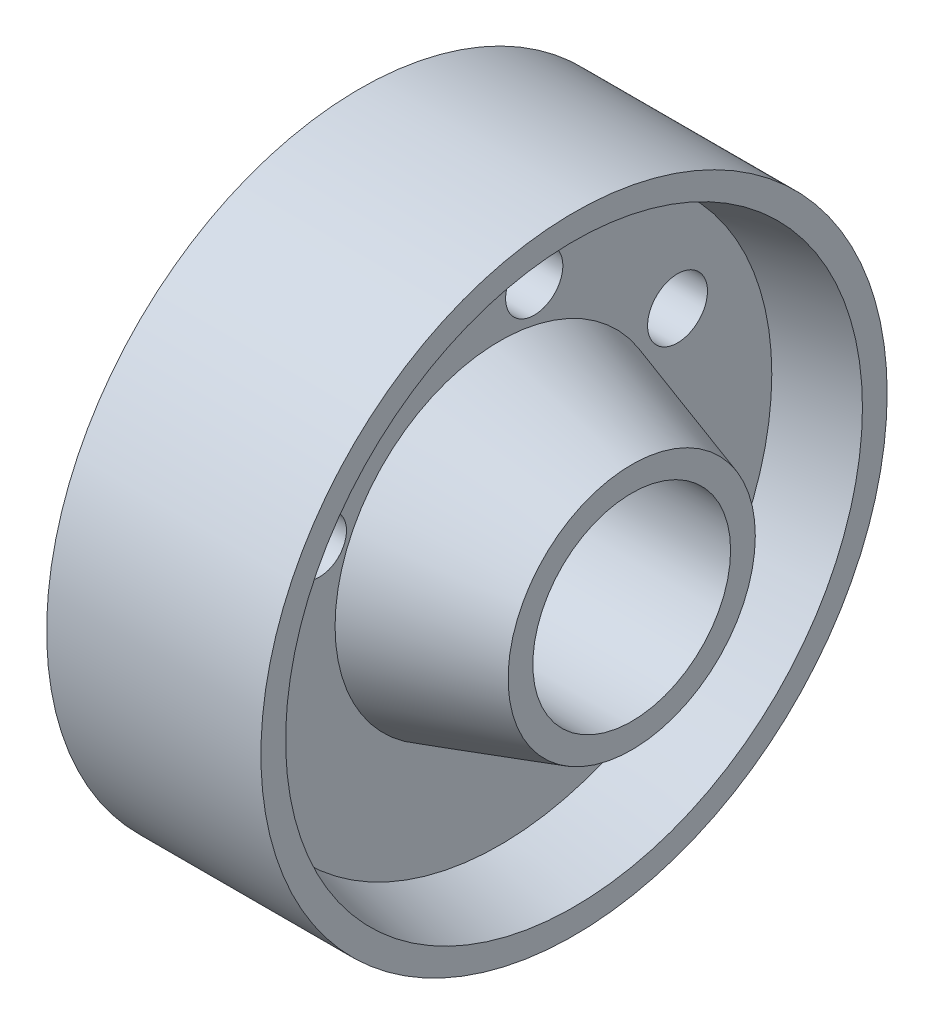
SolidWorks part; units mm, degrees
ref_plane "Front Plane" through (0, 0, 0) normal (0, 0, 1) x (1, 0, 0)
ref_plane "Top Plane" through (0, 0, 0) normal (0, 1, 0) x (1, 0, 0)
ref_plane "Right Plane" through (0, 0, 0) normal (1, 0, 0) x (0, 0, -1)
sketch "Sketch1" plane through (0, 0, 0) normal (0, 0, 1) x (1, 0, 0)
  line L0 (29.5364, 0) -> (0, 0) construction
  line L1 (0, 0) -> (0, 28.5061) construction
  line L2 (20, 12) -> (20, 15)
  line L3 (-20, 12) -> (-20, 15)
  line L4 (20, 15) -> (4, 20)
  line L5 (-20, 15) -> (-4, 20)
  line L6 (4, 20) -> (4, 33)
  line L7 (-4, 20) -> (-4, 33)
  line L8 (4, 33) -> (13, 35)
  line L9 (-4, 33) -> (-13, 35)
  line L10 (13, 35) -> (13, 38)
  line L11 (-13, 35) -> (-13, 38)
  line L12 (13, 38) -> (-13, 38)
  line L13 (-20, 12) -> (20, 12)
  dimension "D1" = 26
  dimension "D2" = 40
  dimension "D3" = 8
  dimension "D4" = 24
  dimension "D5" = 30
  dimension "D6" = 40
  dimension "D7" = 66
  dimension "D8" = 70
  dimension "D9" = 76
revolve "Revolve2" add sketch "Sketch1" angle 360 about L0
sketch "Sketch2" plane through (4, 0, 0) normal (1, 0, 0) x (0, 0, -1)
  circle A0 centre (-21.868, 9.3816) radius 3.2532
  circle A1 centre (4.1693, 24.0897) radius 3.4759
  circle A2 centre (21.5585, 12.6348) radius 3.6339
extrude "Cut-Extrude1" cut sketch "Sketch2" against normal through all both and the other way through all
